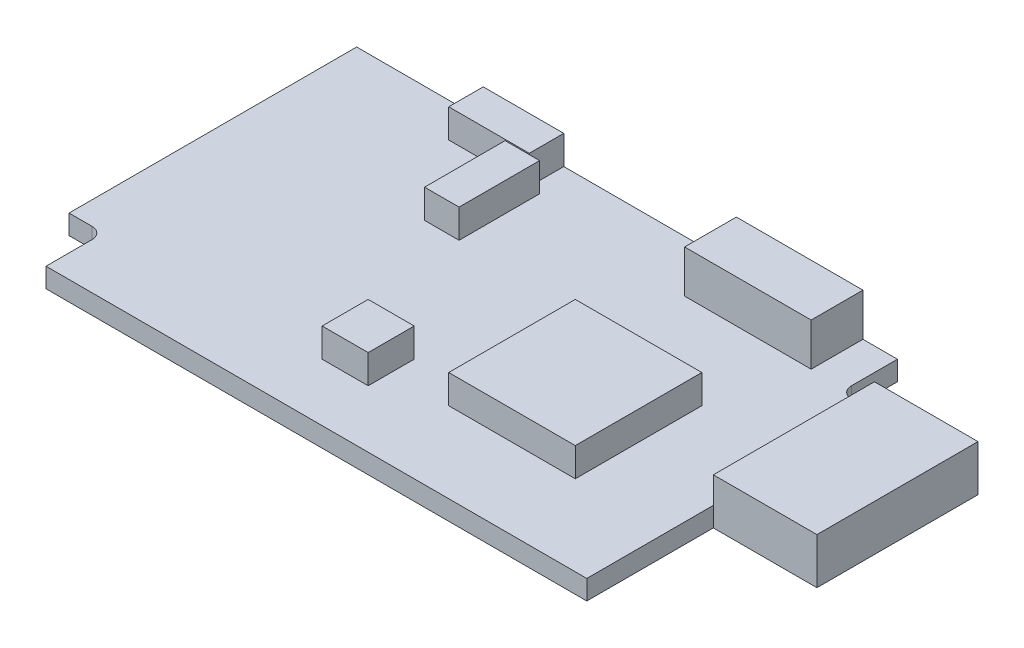
SolidWorks part; units mm, degrees
ref_plane "Front Plane" through (0, 0, 0) normal (0, 0, 1) x (1, 0, 0)
ref_plane "Top Plane" through (0, 0, 0) normal (0, 1, 0) x (1, 0, 0)
ref_plane "Right Plane" through (0, 0, 0) normal (1, 0, 0) x (0, 0, -1)
sketch "Sketch1" plane through (0, 0, 0) normal (0, 1, 0) x (1, 0, 0)
  line L0 (0, 5) -> (3, 5)
  line L1 (3, 0) -> (50, 0)
  line L2 (0, 5) -> (0, 30)
  line L3 (0, 30) -> (47, 30)
  line L4 (50, 0) -> (50, 25)
  line L5 (3, 5) -> (3, 0)
  line L6 (47, 30) -> (47, 25)
  line L7 (47, 25) -> (50, 25)
  dimension "D1" = 50
  dimension "D2" = 30
  dimension "D3" = 3
  dimension "D4" = 5
  dimension "D5" = 5
  dimension "D6" = 3
extrude "Boss-Extrude2" add sketch "Sketch1" along normal blind 1.7
fillet "Fillet2" radius 1 2 edges at (47, 0.85, -25) (3, 0.85, -5)
sketch "Sketch2" plane through (0, 1.7, 0) normal (0, 1, 0) x (1, 0, 0)
  line L0 (0, 30) -> (0, 5) construction
  line L1 (11, 30) -> (18, 30)
  line L2 (11, 30) -> (11, 27)
  line L3 (11, 27) -> (18, 27)
  line L4 (18, 30) -> (18, 27)
  line L5 (16, 26.9) -> (19, 26.9)
  line L6 (16, 26.9) -> (16, 19.9)
  line L7 (16, 19.9) -> (19, 19.9)
  line L8 (19, 26.9) -> (19, 19.9)
  line L9 (47, 30) -> (0, 30) construction
  line L10 (3, 0) -> (50, 0) construction
  line L11 (22, 9) -> (26, 9)
  line L12 (22, 9) -> (22, 5)
  line L13 (22, 5) -> (26, 5)
  line L14 (26, 9) -> (26, 5)
  line L16 (31, 18) -> (42, 18)
  line L17 (31, 18) -> (31, 7)
  line L18 (31, 7) -> (42, 7)
  line L19 (42, 18) -> (42, 7)
  dimension "D1" = 7
  dimension "D2" = 3
  dimension "D3" = 3
  dimension "D4" = 7
  dimension "D5" = 11
  dimension "D6" = 3.1
  dimension "D7" = 16
  dimension "D8" = 4
  dimension "D9" = 4
  dimension "D10" = 22
  dimension "D11" = 5
  dimension "D12" = 11
  dimension "D13" = 11
  dimension "D14" = 31
  dimension "D15" = 7
extrude "Boss-Extrude3" add sketch "Sketch2" along normal blind 2.5
sketch "Sketch3" plane through (0, 1.7, -31.7) normal (0, 1, 0) x (-1, 0, 0)
  line L1 (-44, 6.2) -> (-33, 6.2)
  line L2 (-44, 6.2) -> (-44, 1.7)
  line L3 (-44, 1.7) -> (-33, 1.7)
  line L4 (-33, 6.2) -> (-33, 1.7)
  line L5 (-47, 1.7) -> (0, 1.7) construction
  line L6 (-47, 5.7) -> (-47, 1.7) construction
  dimension "D1" = 11
  dimension "D2" = 4.5
  dimension "D3" = 3
extrude "Boss-Extrude4" add sketch "Sketch3" along normal blind 3.7
sketch "Sketch4" plane through (50, 0, 0) normal (1, 0, 0) x (0, 0, -1)
  line L0 (0, 0) -> (25, 0) construction
  line L1 (11, 0) -> (25, 0)
  line L2 (11, 0) -> (11, 4)
  line L3 (11, 4) -> (25, 4)
  line L4 (25, 0) -> (25, 4)
  dimension "D1" = 4
  dimension "D2" = 14
extrude "Boss-Extrude5" add sketch "Sketch4" along normal blind 9
